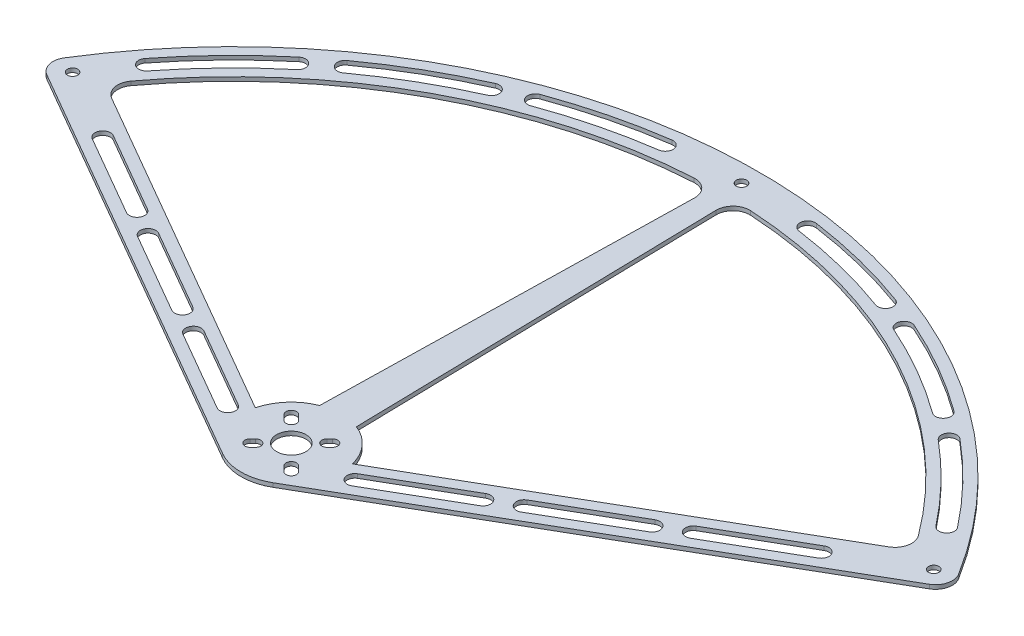
SolidWorks part; units mm, degrees
ref_plane "前视基准面" through (0, 0, 0) normal (0, 0, 1) x (1, 0, 0)
ref_plane "上视基准面" through (0, 0, 0) normal (0, 1, 0) x (1, 0, 0)
ref_plane "右视基准面" through (0, 0, 0) normal (1, 0, 0) x (0, 0, -1)
other "Configuration Table"
sketch "草图1" plane through (0, 0, 0) normal (0, 1, 0) x (1, 0, 0)
  line L0 (-7.5, 4.3301) -> (-131.8423, 76.1192)
  line L1 (7.5, 4.3301) -> (131.8423, 76.1192)
  line L3 (0, 0) -> (32.0697, 0) construction
  line L4 (0, 0) -> (0, 49.7171) construction
  line L5 (-14.52, 21.0848) -> (-116.1002, 79.7322)
  line L6 (14.52, 21.0848) -> (116.1002, 79.7322)
  line L7 (-5.5, 31.2758) -> (-3.0908, 146.2879)
  line L8 (5.5, 31.2758) -> (3.0908, 146.2879)
  line L9 (-6.0415, 11.2791) -> (12.4425, 29.763) construction
  line L10 (2, 13.8564) -> (120.8587, 82.4795) construction
  line L11 (-2, 13.8564) -> (-120.8587, 82.4795) construction
  line L12 (0, 17.3205) -> (-19.1045, 36.425) construction
  line L13 (5.3387, 22.6592) -> (6.1518, 23.4723) construction
  line L16 (4.2426, 23.7552) -> (5.0558, 24.5684)
  line L19 (6.4347, 21.5631) -> (7.2478, 22.3763)
  line L22 (-5.3387, 11.9819) -> (-6.1518, 11.1687) construction
  line L23 (-6.4347, 13.0779) -> (-7.2478, 12.2647)
  line L24 (-4.2426, 10.8858) -> (-5.0558, 10.0727)
  line L25 (-7.3893, 24.7098) -> (-5.869, 23.1895) construction
  line L26 (-6.2933, 25.8058) -> (-4.773, 24.2855)
  line L27 (-8.4853, 23.6138) -> (-6.965, 22.0935)
  line L28 (7.3893, 9.9312) -> (5.869, 11.4515) construction
  line L29 (8.4853, 11.0273) -> (6.965, 12.5475)
  line L30 (6.2933, 8.8352) -> (4.773, 10.3555)
  line L31 (-93.375, 60.261) -> (-37.0409, 27.7364) construction
  line L32 (-43.2487, 31.3205) -> (-19, 17.3205) construction
  line L33 (-42.0987, 33.3124) -> (-17.85, 19.3124)
  line L34 (-44.3987, 29.3286) -> (-20.15, 15.3286)
  line L35 (-75.2917, 49.8205) -> (-51.0429, 35.8205) construction
  line L36 (-74.1417, 51.8124) -> (-49.8929, 37.8124)
  line L37 (-76.4417, 47.8286) -> (-52.1929, 33.8286)
  line L38 (-107.3346, 68.3205) -> (-83.0859, 54.3205) construction
  line L39 (-106.1846, 70.3124) -> (-81.9359, 56.3124)
  line L40 (-108.4846, 66.3286) -> (-84.2359, 52.3286)
  line L43 (-4.75, 9.0933) -> (-128.6441, 80.6236) construction
  line L44 (4.75, 9.0933) -> (128.6441, 80.6236) construction
  line L45 (0, 0) -> (-93.3738, 161.7282) construction
  line L46 (43.2487, 31.3205) -> (19, 17.3205) construction
  line L49 (75.2917, 49.8205) -> (51.0429, 35.8205) construction
  line L50 (74.1417, 51.8124) -> (49.8929, 37.8124)
  line L51 (76.4417, 47.8286) -> (52.1929, 33.8286)
  line L52 (107.3346, 68.3205) -> (83.0859, 54.3205) construction
  line L53 (106.1846, 70.3124) -> (81.9359, 56.3124)
  line L54 (108.4846, 66.3286) -> (84.2359, 52.3286)
  line L55 (93.375, 60.261) -> (37.0409, 27.7364) construction
  line L56 (42.0987, 33.3124) -> (17.85, 19.3124)
  line L57 (44.3987, 29.3286) -> (20.15, 15.3286)
  line L58 (-7.5, 4.3301) -> (-136.2436, 78.6603) construction
  line L59 (7.5, 4.3301) -> (136.2436, 78.6603) construction
  arc A0 (133.5881, 83.0901) -> (-133.5881, 83.0901) centre (0, 0) ccw
  arc A2 (-7.5, 4.3301) -> (7.5, 4.3301) centre (0, 17.3205) ccw
  circle A4 centre (0, 17.3205) radius 15
  arc A5 (117.6195, 87.0365) -> (-117.6195, 87.0365) centre (0, 0) ccw
  circle A7 centre (0, 17.3205) radius 4.4
  arc A14 (-2, 13.8564) -> (2, 13.8564) centre (0, 17.3205) ccw construction
  arc A15 (4.2426, 23.7552) -> (6.4347, 21.5631) centre (5.3387, 22.6592) ccw
  arc A16 (7.2478, 22.3763) -> (5.0558, 24.5684) centre (6.1518, 23.4723) ccw
  arc A17 (-6.4347, 13.0779) -> (-4.2426, 10.8858) centre (-5.3387, 11.9819) cw
  arc A18 (-5.0558, 10.0727) -> (-7.2478, 12.2647) centre (-6.1518, 11.1687) cw
  arc A19 (-6.2933, 25.8058) -> (-8.4853, 23.6138) centre (-7.3893, 24.7098) ccw
  arc A20 (-6.965, 22.0935) -> (-4.773, 24.2855) centre (-5.869, 23.1895) ccw
  arc A21 (8.4853, 11.0273) -> (6.2933, 8.8352) centre (7.3893, 9.9312) cw
  arc A22 (4.773, 10.3555) -> (6.965, 12.5475) centre (5.869, 11.4515) cw
  arc A23 (-42.0987, 33.3124) -> (-44.3987, 29.3286) centre (-43.2487, 31.3205) ccw
  arc A24 (-20.15, 15.3286) -> (-17.85, 19.3124) centre (-19, 17.3205) ccw
  arc A25 (-74.1417, 51.8124) -> (-76.4417, 47.8286) centre (-75.2917, 49.8205) ccw
  arc A26 (-52.1929, 33.8286) -> (-49.8929, 37.8124) centre (-51.0429, 35.8205) ccw
  arc A27 (-106.1846, 70.3124) -> (-108.4846, 66.3286) centre (-107.3346, 68.3205) ccw
  arc A28 (-84.2359, 52.3286) -> (-81.9359, 56.3124) centre (-83.0859, 54.3205) ccw
  arc A29 (128.6441, 80.6236) -> (-128.6441, 80.6236) centre (0, 0) ccw construction
  arc A30 (-4.75, 9.0933) -> (4.75, 9.0933) centre (0, 17.3205) ccw
  arc A31 (-119.5561, 93.5725) -> (-97.2875, 116.5531) centre (0, 0) cw construction
  arc A32 (-98.7613, 118.3188) -> (-121.3673, 94.99) centre (0, 0) ccw
  arc A33 (-95.8136, 114.7873) -> (-117.7449, 92.1549) centre (0, 0) ccw
  arc A34 (-95.8136, 114.7873) -> (-98.7613, 118.3188) centre (-97.2875, 116.5531) ccw
  arc A35 (-121.3673, 94.99) -> (-117.7449, 92.1549) centre (-119.5561, 93.5725) ccw
  arc A36 (-89.3439, 122.7482) -> (-61.6311, 138.7482) centre (0, 0) cw construction
  arc A37 (-62.5648, 140.8502) -> (-90.6974, 124.6078) centre (0, 0) ccw
  arc A38 (-60.6974, 136.6463) -> (-87.9904, 120.8887) centre (0, 0) ccw
  arc A39 (-60.6974, 136.6463) -> (-62.5648, 140.8502) centre (-61.6311, 138.7482) ccw
  arc A40 (-90.6974, 124.6078) -> (-87.9904, 120.8887) centre (-89.3439, 122.7482) ccw
  arc A41 (-52.2942, 142.5299) -> (-21.2581, 150.3248) centre (0, 0) cw construction
  arc A42 (-21.5801, 152.6022) -> (-53.0864, 144.6892) centre (0, 0) ccw
  arc A43 (-20.936, 148.0475) -> (-51.502, 140.3707) centre (0, 0) ccw
  arc A44 (-20.936, 148.0475) -> (-21.5801, 152.6022) centre (-21.2581, 150.3248) ccw
  arc A45 (-53.0864, 144.6892) -> (-51.502, 140.3707) centre (-52.2942, 142.5299) ccw
  circle A46 centre (-128.6441, 80.6236) radius 1.55
  circle A47 centre (0, 151.8205) radius 1.55
  circle A48 centre (128.6441, 80.6236) radius 1.55
  arc A51 (74.1417, 51.8124) -> (76.4417, 47.8286) centre (75.2917, 49.8205) cw
  arc A52 (52.1929, 33.8286) -> (49.8929, 37.8124) centre (51.0429, 35.8205) cw
  arc A53 (106.1846, 70.3124) -> (108.4846, 66.3286) centre (107.3346, 68.3205) cw
  arc A54 (84.2359, 52.3286) -> (81.9359, 56.3124) centre (83.0859, 54.3205) cw
  arc A55 (52.2942, 142.5299) -> (21.2581, 150.3248) centre (0, 0) ccw construction
  arc A56 (21.5801, 152.6022) -> (53.0864, 144.6892) centre (0, 0) cw
  arc A57 (20.936, 148.0475) -> (51.502, 140.3707) centre (0, 0) cw
  arc A58 (20.936, 148.0475) -> (21.5801, 152.6022) centre (21.2581, 150.3248) cw
  arc A59 (53.0864, 144.6892) -> (51.502, 140.3707) centre (52.2942, 142.5299) cw
  arc A60 (89.3439, 122.7482) -> (61.6311, 138.7482) centre (0, 0) ccw construction
  arc A61 (62.5648, 140.8502) -> (90.6974, 124.6078) centre (0, 0) cw
  arc A62 (60.6974, 136.6463) -> (87.9904, 120.8887) centre (0, 0) cw
  arc A63 (60.6974, 136.6463) -> (62.5648, 140.8502) centre (61.6311, 138.7482) cw
  arc A64 (90.6974, 124.6078) -> (87.9904, 120.8887) centre (89.3439, 122.7482) cw
  arc A65 (119.5561, 93.5725) -> (97.2875, 116.5531) centre (0, 0) ccw construction
  arc A66 (98.7613, 118.3188) -> (121.3673, 94.99) centre (0, 0) cw
  arc A67 (95.8136, 114.7873) -> (117.7449, 92.1549) centre (0, 0) cw
  arc A68 (95.8136, 114.7873) -> (98.7613, 118.3188) centre (97.2875, 116.5531) cw
  arc A69 (121.3673, 94.99) -> (117.7449, 92.1549) centre (119.5561, 93.5725) cw
  arc A70 (42.0987, 33.3124) -> (44.3987, 29.3286) centre (43.2487, 31.3205) cw
  arc A71 (20.15, 15.3286) -> (17.85, 19.3124) centre (19, 17.3205) cw
  arc A72 (136.2436, 78.6603) -> (-136.2436, 78.6603) centre (0, 0) ccw construction
  arc A73 (-131.8423, 76.1192) -> (-133.5881, 83.0901) centre (-129.3423, 80.4493) cw
  arc A74 (131.8423, 76.1192) -> (133.5881, 83.0901) centre (129.3423, 80.4493) ccw
  arc A75 (120.8587, 82.4795) -> (-120.8587, 82.4795) centre (0, 0) ccw construction
  arc A76 (117.6195, 87.0365) -> (116.1002, 79.7322) centre (113.6002, 84.0623) cw
  arc A77 (-117.6195, 87.0365) -> (-116.1002, 79.7322) centre (-113.6002, 84.0623) ccw
  point P31 (5.7452, 23.0658)
  point P38 (-5.7452, 11.5753)
  point P43 (-6.6291, 23.9496)
  point P50 (0, 157.3205)
  point P53 (6.6291, 10.6914)
  point P62 (-31.1244, 24.3205)
  point P69 (-63.1673, 42.8205)
  point P76 (-95.2102, 61.3205)
  point P89 (-109.0289, 105.6511)
  point P97 (-75.9103, 131.4804)
  point P105 (-36.9821, 147.2474)
  point P118 (31.1244, 24.3205)
  point P127 (63.1673, 42.8205)
  point P134 (95.2102, 61.3205)
  point P141 (36.9821, 147.2474)
  point P148 (75.9103, 131.4804)
  point P155 (109.0289, 105.6511)
  dimension "D3" = 15
  dimension "D4" = 11
  dimension "D7" = 1.55
  dimension "D8" = 140
  dimension "D9" = 7.55
  dimension "D10" = 8.7
  dimension "D11" = 1.55
  dimension "D14" = 1.2
  dimension "D18" = 3.1
  dimension "D19" = 3.1
  dimension "D20" = 2.3
  dimension "D21" = 37
  dimension "D22" = 37
  dimension "D23" = 2.3
  dimension "D24" = 42
  dimension "D25" = 42
  dimension "D26" = 2.3
  dimension "D27" = 30
  dimension "D30" = 5
  dimension "D31" = 5
  dimension "D32" = 8.8
  dimension "D1" = 30
  dimension "D2" = 30
  dimension "D5" = 45
  dimension "D6" = 45
  dimension "D12" = 8.3
  dimension "D13" = 2.15
  dimension "D15" = 5.5
  dimension "D16" = 5.5
  dimension "D28" = 32
  dimension "D29" = 28
  dimension "D17" = 5.5
extrude "凸台-拉伸1" add sketch "草图1" along normal blind 1.2
fillet "圆角1" radius 5 2 edges at (3.0908, 0.6, -146.2879) (-3.0908, 0.6, -146.2879)
